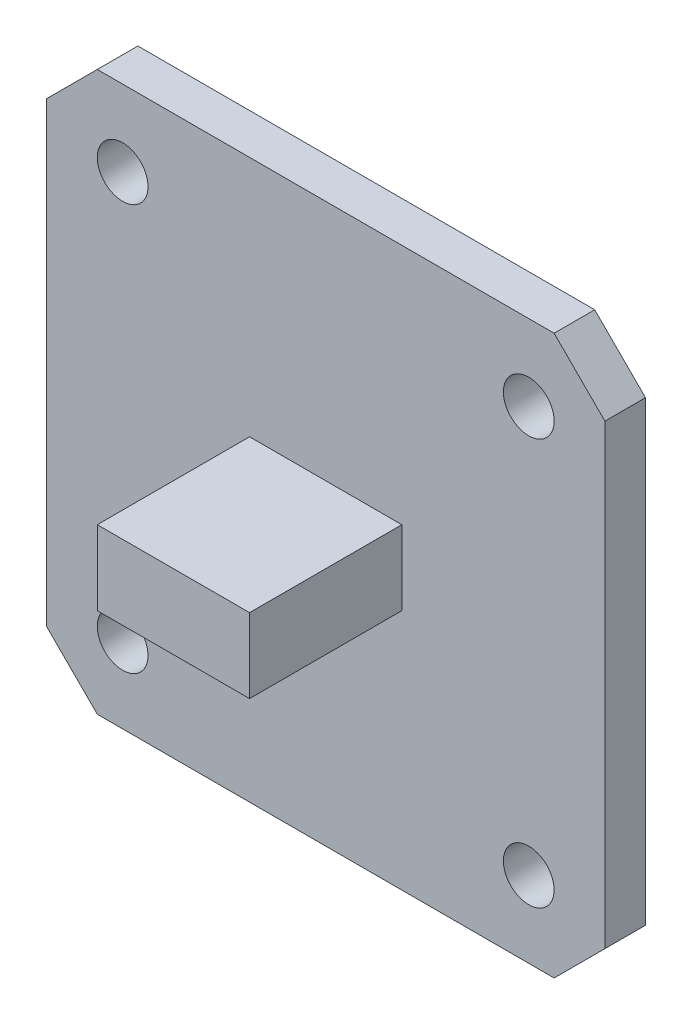
SolidWorks part; units mm, degrees
ref_plane "Plan de face" through (0, 0, 0) normal (0, 0, 1) x (1, 0, 0)
ref_plane "Plan de dessus" through (0, 0, 0) normal (0, 1, 0) x (1, 0, 0)
ref_plane "Plan de droite" through (0, 0, 0) normal (1, 0, 0) x (0, 0, -1)
sketch "Esquisse1" plane through (0, 0, 0) normal (0, 0, 1) x (1, 0, 0)
  line L0 (-18.7422, 0) -> (55.4216, 0) construction
  line L1 (-20.2369, 33) -> (51.9721, 33) construction
  line L2 (33, 39.6386) -> (33, -11.7857) construction
  line L3 (0, -11.7857) -> (0, 39.6386) construction
  line L4 (0, 30) -> (0, 3)
  line L5 (0, 3) -> (3, 0)
  line L6 (3, 0) -> (30, 0)
  line L7 (30, 0) -> (33, 3)
  line L8 (33, 3) -> (33, 30)
  line L9 (33, 30) -> (30, 33)
  line L10 (30, 33) -> (3, 33)
  line L11 (3, 33) -> (0, 30)
  line L12 (-7.4241, 30) -> (46.1755, 30) construction
  line L13 (46.1755, 3) -> (-7.4241, 3) construction
  line L14 (3, 37.6874) -> (3, -3.9473) construction
  line L15 (30, -4.8742) -> (30, 36.6584) construction
  line L16 (16.5, 33) -> (16.5, 0) construction
  line L17 (0, 16.5) -> (33, 16.5) construction
  circle A0 centre (4.5, 28.5) radius 1.5
  circle A1 centre (28.5, 28.5) radius 1.5
  circle A2 centre (4.5, 4.5) radius 1.5
  circle A3 centre (28.5, 4.5) radius 1.5
  dimension "D7" = 12
  dimension "D9" = 3
  dimension "D1" = 33
  dimension "D2" = 33
  dimension "D3" = 3
  dimension "D4" = 3
  dimension "D5" = 3
  dimension "D6" = 3
  dimension "D8" = 12
extrude "Boss.-Extru.1" add sketch "Esquisse1" along normal blind 2.4
sketch "Esquisse2" plane through (0, 0, 2.4) normal (0, 0, 1) x (1, 0, 0)
  line L0 (16.5, 33) -> (16.5, 0) construction
  line L1 (30, 33) -> (3, 33) construction
  line L2 (3, 0) -> (30, 0) construction
  line L3 (33, 16.5) -> (0, 16.5) construction
  line L4 (33, 3) -> (33, 30) construction
  line L5 (0, 30) -> (0, 3) construction
  line L7 (12, 18.7) -> (21, 18.7)
  line L8 (12, 18.7) -> (12, 14.3)
  line L9 (12, 14.3) -> (21, 14.3)
  line L10 (21, 18.7) -> (21, 14.3)
  point P16 (0, 0)
  point P17 (0, 0)
  dimension "D1" = 9
  dimension "D2" = 4.4
extrude "Boss.-Extru.2" add sketch "Esquisse2" along normal blind 9
